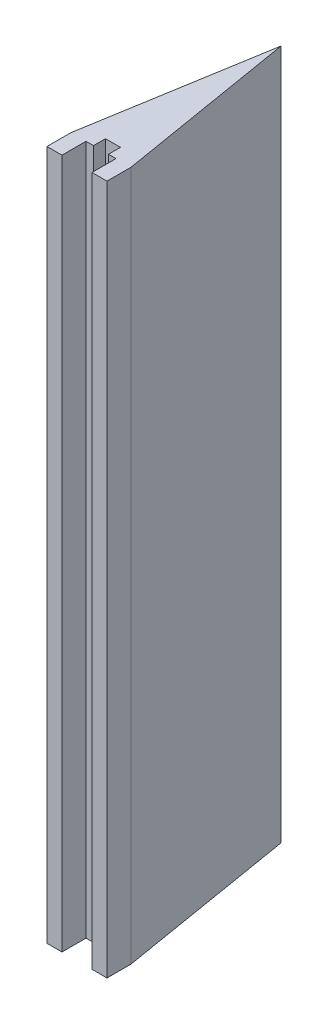
SolidWorks part; units mm, degrees
material "6061-T6 (SS)"
ref_plane "Front Plane" through (0, 0, 0) normal (0, 0, 1) x (1, 0, 0)
ref_plane "Top Plane" through (0, 0, 0) normal (0, 1, 0) x (1, 0, 0)
ref_plane "Right Plane" through (0, 0, 0) normal (1, 0, 0) x (0, 0, -1)
sketch "Sketch1" plane through (0, 0, 0) normal (0, 1, 0) x (1, 0, 0)
  line L0 (0, 0) -> (0, 38.1) construction
  line L1 (0, 38.1) -> (-6.35, 0)
  line L2 (0, 38.1) -> (6.35, 0)
  line L3 (0, 18.7872) -> (3.2182, -0.522) construction
  line L4 (0, 18.7872) -> (-3.2182, -0.522) construction
  line L5 (0, 0) -> (3.175, 0) construction
  line L6 (0, 0) -> (-3.175, 0) construction
  line L7 (-3.175, 0) -> (-3.175, -5.08)
  line L8 (-3.175, -5.08) -> (-6.35, -5.08)
  line L9 (-6.35, -5.08) -> (-6.35, 0)
  line L10 (3.175, 0) -> (3.175, -5.08)
  line L11 (3.175, -5.08) -> (6.35, -5.08)
  line L12 (6.35, -5.08) -> (6.35, 0)
  line L13 (-3.175, 0) -> (-1.5875, 0)
  line L19 (-1.5875, 0) -> (-1.5875, 2.54)
  line L20 (-1.5875, 2.54) -> (1.5875, 2.54)
  line L21 (1.5875, 2.54) -> (1.5875, 0)
  line L22 (1.5875, 0) -> (3.175, 0)
  dimension "D7" = 1.5875
  dimension "D1" = 38.1
  dimension "D2" = 6.35
  dimension "D3" = 6.35
  dimension "D5" = 3.175
  dimension "D6" = 3.175
  dimension "D8" = 5.08
  dimension "D9" = 5.08
  dimension "D10" = 2.54
  dimension "D11" = 3.175
  dimension "D12" = 1.5875
  dimension "D4" = 3.175
extrude "Boss-Extrude1" add sketch "Sketch1" along normal blind 146.05
